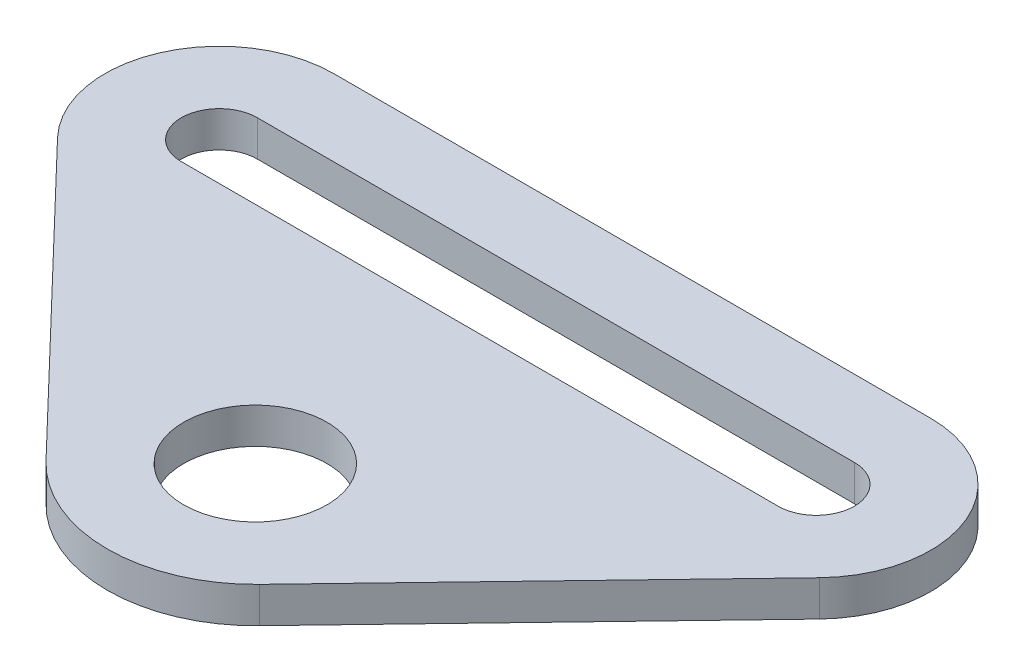
SolidWorks part; units mm, degrees
ref_plane "Front Plane" through (0, 0, 0) normal (0, 0, 1) x (1, 0, 0)
ref_plane "Top Plane" through (0, 0, 0) normal (0, 1, 0) x (1, 0, 0)
ref_plane "Right Plane" through (0, 0, 0) normal (1, 0, 0) x (0, 0, -1)
sketch "Sketch1" plane through (0, 0, 0) normal (0, 1, 0) x (1, 0, 0)
  line L0 (-25, 21.9845) -> (25, 21.9845) construction
  line L1 (-25, 25.1689) -> (25, 25.1689)
  line L2 (-25, 18.8) -> (25, 18.8)
  line L3 (25, 21.9845) -> (-25, 21.9845) construction
  line L5 (25, 31.5689) -> (-25, 31.5689)
  line L6 (-8.9467, -8.5858) -> (-31.9153, 15.3481)
  line L7 (0, -22.8603) -> (0, 22.8603) construction
  line L8 (8.9467, -8.5858) -> (31.9153, 15.3481)
  arc A0 (-25, 25.1689) -> (-25, 18.8) centre (-25, 21.9845) ccw
  arc A1 (25, 18.8) -> (25, 25.1689) centre (25, 21.9845) ccw
  arc A2 (-8.9467, -8.5858) -> (8.9467, -8.5858) centre (0, 0) ccw
  circle A3 centre (0, 0) radius 6
  arc A4 (31.9153, 15.3481) -> (25, 31.5689) centre (25, 21.9845) ccw
  arc A5 (-25, 31.5689) -> (-31.9153, 15.3481) centre (-25, 21.9845) ccw
  point P2 (0, 21.9845)
  point P13 (0, 21.9845)
  point P18 (0, 0)
  point P19 (0, 0)
  point P22 (0, 0)
  dimension "D1" = 6.4
  dimension "D2" = 6.4
  dimension "D3" = 12
  dimension "D4" = 50
extrude "Boss-Extrude1" add sketch "Sketch1" along normal blind 3
